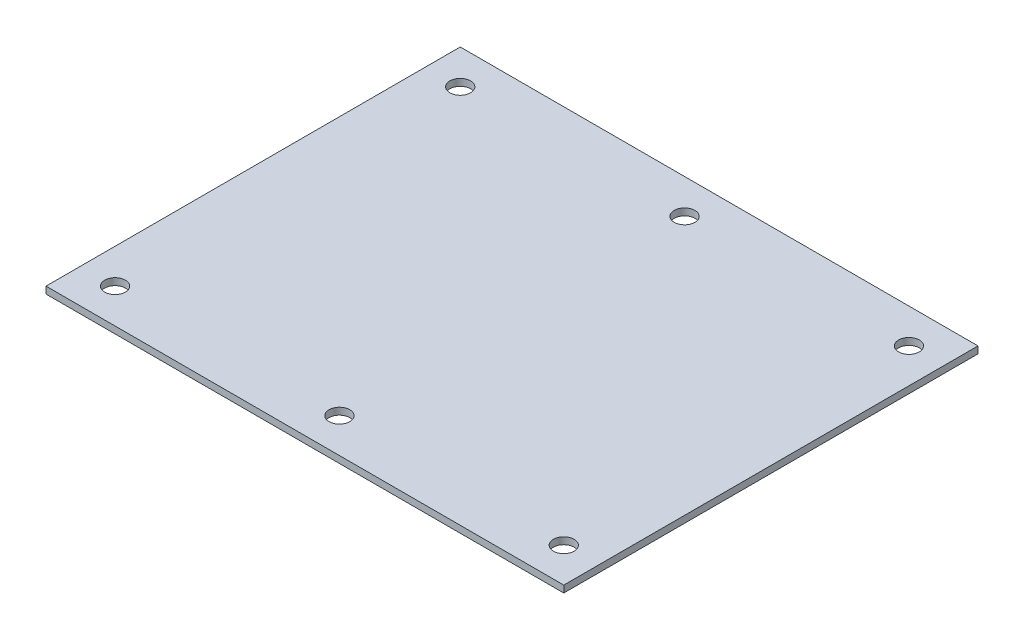
SolidWorks part; units mm, degrees
ref_plane "前视基准面" through (0, 0, 0) normal (0, 0, 1) x (1, 0, 0)
ref_plane "上视基准面" through (0, 0, 0) normal (0, 1, 0) x (1, 0, 0)
ref_plane "右视基准面" through (0, 0, 0) normal (1, 0, 0) x (0, 0, -1)
sketch "草图1" plane through (0, 0, 0) normal (0, 1, 0) x (1, 0, 0)
  line L1 (-37.5, 30) -> (37.5, 30)
  line L2 (-37.5, 30) -> (-37.5, -30)
  line L3 (-37.5, -30) -> (37.5, -30)
  line L4 (37.5, 30) -> (37.5, -30)
  line L5 (-37.5, 30) -> (37.5, -30) construction
  line L6 (-37.5, -30) -> (37.5, 30) construction
  point P0 (0, 0)
  dimension "D1" = 75
  dimension "D2" = 60
extrude "凸台-拉伸1" add sketch "草图1" along normal blind 1
sketch "草图2" plane through (0, 0, 0) normal (0, 1, 0) x (1, 0, 0)
  line L0 (37.5, 30) -> (-37.5, 30) construction
  line L3 (-37.5, 30) -> (-37.5, -30) construction
  line L4 (0, 0) -> (-11.2466, 0) construction
  line L5 (0, 30) -> (0, 9.5695) construction
  line L6 (37.5, -30) -> (37.5, 30) construction
  circle A0 centre (-32.5, 25) radius 1.5
  circle A1 centre (-32.5, -25) radius 1.5
  circle A2 centre (32.5, -25) radius 1.5
  circle A3 centre (32.5, 25) radius 1.5
  circle A4 centre (0, -25) radius 1.5
  circle A5 centre (0, 25) radius 1.5
  dimension "D1" = 3
  dimension "D2" = 5
  dimension "D3" = 5
  dimension "D4" = 37.5
  dimension "D5" = 2
  dimension "D6" = 2
extrude "切除-拉伸1" cut sketch "草图2" along normal through all
